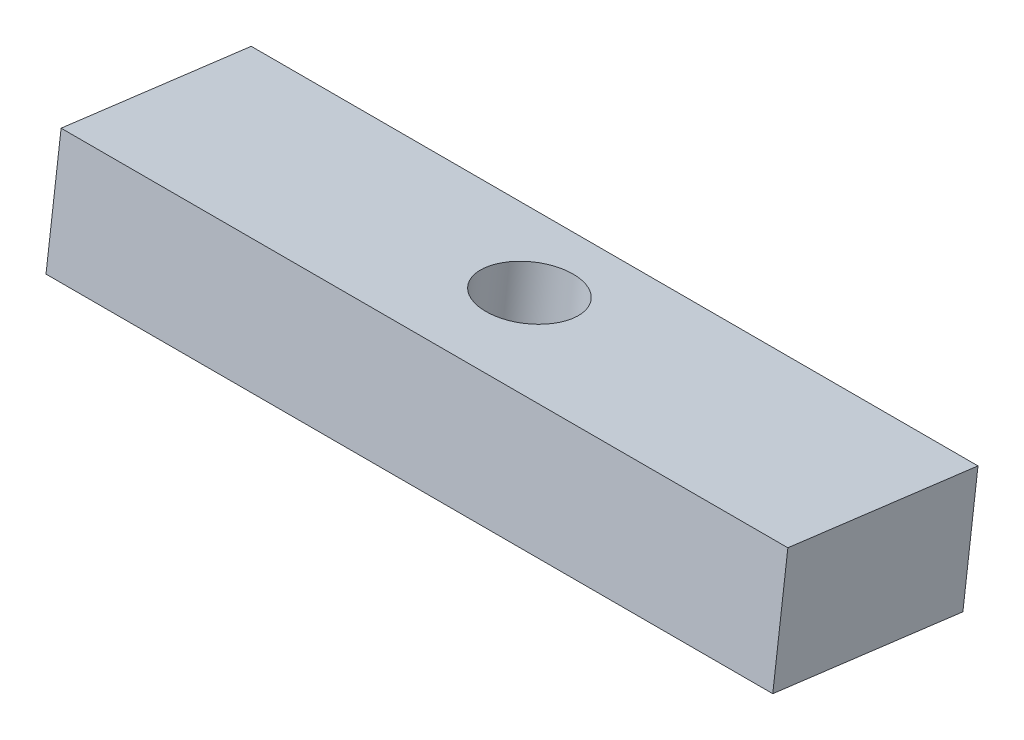
SolidWorks part; units mm, degrees
ref_plane "Front Plane" through (0, 0, 0) normal (0, 0, 1) x (1, 0, 0)
ref_plane "Top Plane" through (0, 0, 0) normal (0, 1, 0) x (1, 0, 0)
ref_plane "Right Plane" through (0, 0, 0) normal (1, 0, 0) x (0, 0, -1)
sketch "Sketch1" plane through (0, 184.7231, -23.4616) normal (0, -0.992, 0.126) x (1, 0, 0)
  line L0 (-1.3, -106.2034) -> (-11.8, -106.2034) construction
  line L1 (2.55, -106.2034) -> (-15.65, -106.2034)
  line L2 (-1.3, -111.0034) -> (-6, -111.0034) construction
  line L3 (-7.1, -111.0034) -> (-11.8, -111.0034) construction
  line L4 (2.55, -111.0034) -> (-6, -111.0034)
  line L5 (-7.1, -111.0034) -> (-15.65, -111.0034)
  line L6 (-15.65, 3.7966) -> (-15.65, -112.2034) construction
  line L7 (2.55, 3.7966) -> (2.55, -112.2034) construction
  line L8 (-15.65, -106.2034) -> (-15.65, -111.0034)
  line L9 (2.55, -106.2034) -> (2.55, -111.0034)
  line L10 (-7.1, -111.0034) -> (-6, -111.0034)
  circle A0 centre (-6.55, -108.8534) radius 1.1
  arc A1 (-6, -109.806) -> (-7.1, -109.806) centre (-6.55, -108.8534) ccw construction
extrude "Boss-Extrude1" add sketch "Sketch1" along normal blind 3
